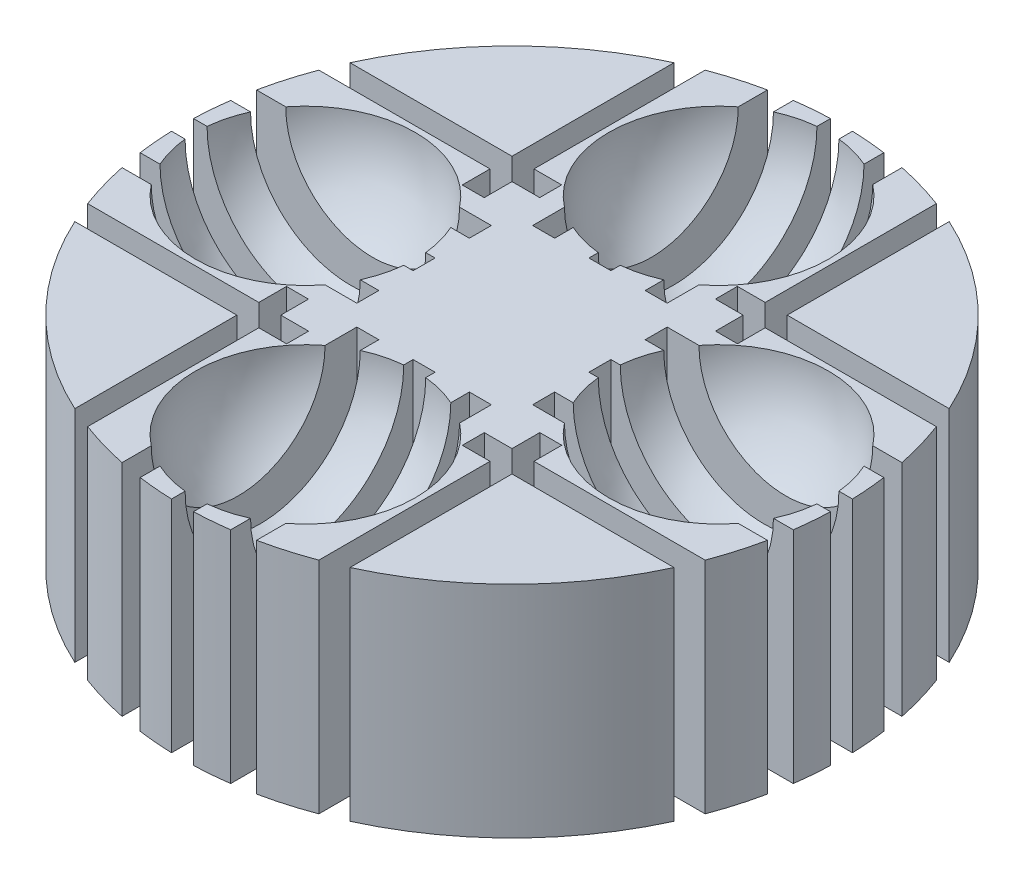
SolidWorks part; units mm, degrees
ref_plane "Front Plane" through (0, 0, 0) normal (0, 0, 1) x (1, 0, 0)
ref_plane "Top Plane" through (0, 0, 0) normal (0, 1, 0) x (1, 0, 0)
ref_plane "Right Plane" through (0, 0, 0) normal (1, 0, 0) x (0, 0, -1)
sketch "Sketch1" plane through (0, 0, 0) normal (0, 1, 0) x (1, 0, 0)
  circle A0 centre (0, 0) radius 95.25
extrude "Boss-Extrude1" add sketch "Sketch1" against normal blind 63.5
ref_plane "Plane1" through (0, 0, 59.69) normal (0, 0, 1) x (1, 0, 0)
sketch "Sketch3" plane through (0, 0, 59.69) normal (0, 0, 1) x (1, 0, 0)
  line L0 (0, 0) -> (0, -31.75)
  line L1 (0, 0) -> (31.75, 0)
  arc A0 (0, -31.75) -> (31.75, 0) centre (0, 0) ccw
revolve "Cut-Revolve3" cut sketch "Sketch3" angle 360 about L0
sketch "Sketch7" plane through (0, 0, 0) normal (0, 1, 0) x (1, 0, 0)
  line L0 (-19.431, -25.4) -> (-13.081, -25.4)
  line L21 (-3.175, -25.4) -> (3.175, -25.4)
  line L22 (-3.175, -25.4) -> (-3.175, -127)
  line L23 (-3.175, -127) -> (3.175, -127)
  line L24 (3.175, -25.4) -> (3.175, -127)
  line L25 (-19.431, -25.4) -> (-19.431, -127)
  line L26 (-19.431, -127) -> (-13.081, -127)
  line L27 (-13.081, -25.4) -> (-13.081, -127)
  line L28 (13.081, -25.4) -> (19.431, -25.4)
  line L29 (13.081, -25.4) -> (13.081, -126.2754)
  line L30 (13.081, -126.2754) -> (19.431, -126.2754)
  line L31 (19.431, -25.4) -> (19.431, -126.2754)
  line L32 (33.401, -25.3712) -> (39.751, -25.3712)
  line L33 (33.401, -25.3712) -> (33.401, -126.9712)
  line L34 (33.401, -126.9712) -> (39.751, -126.9712)
  line L35 (39.751, -25.3712) -> (39.751, -126.9712)
  line L36 (-39.751, -25.4) -> (-33.401, -25.4)
  line L37 (-39.751, -25.4) -> (-39.751, -127)
  line L38 (-39.751, -127) -> (-33.401, -127)
  line L39 (-33.401, -25.4) -> (-33.401, -127)
  point P4 (0, -25.4)
  dimension "D1" = 0
  dimension "D2" = 6.35
  dimension "D3" = 101.6
  dimension "D4" = 25.4
  dimension "D5" = 20.32
  dimension "D6" = 20.32
  dimension "D7" = 16.256
  dimension "D8" = 16.256
  dimension "D9" = 0
  dimension "D10" = 0
  dimension "D11" = 0
extrude "Cut-Extrude1" cut sketch "Sketch7" against normal through all
sketch "Sketch9" plane through (0, 0, 0) normal (0, 0, 1) x (1, 0, 0)
  line L0 (0, 4.4133) -> (0, -93.6332) construction
pattern_circular "CirPattern1" count 4 over 360 about axis through (0, 0, 0) along (0, 1, 0) of "Cut-Extrude1", "Cut-Revolve3"
